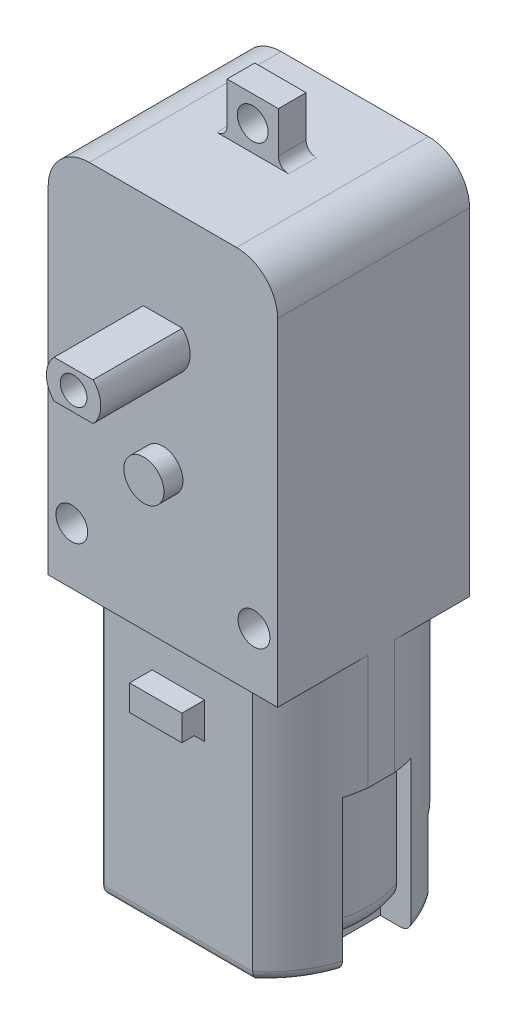
SolidWorks part; units mm, degrees
ref_plane "Front Plane" through (0, 0, 0) normal (0, 0, 1) x (1, 0, 0)
ref_plane "Top Plane" through (0, 0, 0) normal (0, 1, 0) x (1, 0, 0)
ref_plane "Right Plane" through (0, 0, 0) normal (1, 0, 0) x (0, 0, -1)
sketch "Sketch1" plane through (0, 0, 0) normal (0, 0, 1) x (1, 0, 0)
  line L0 (0, -7.1) -> (0, 11.3) construction
  line L1 (-11.175, -25.5) -> (11.175, -25.5)
  line L2 (-11.175, -25.5) -> (-11.175, 7.3)
  line L3 (-7.175, 11.3) -> (7.175, 11.3)
  line L4 (11.175, -25.5) -> (11.175, 7.3)
  line L5 (-11.175, -25.5) -> (11.175, 11.3) construction
  line L6 (-11.175, 11.3) -> (11.175, -25.5) construction
  arc A0 (7.175, 11.3) -> (11.175, 7.3) centre (7.175, 7.3) cw
  arc A1 (-11.175, 7.3) -> (-7.175, 11.3) centre (-7.175, 7.3) cw
  circle A2 centre (-8.875, -20) radius 1.55
  circle A3 centre (8.875, -20) radius 1.55
  point P0 (0, -7.1)
  dimension "D4" = 4
  dimension "D5" = 3.1
  dimension "D1" = 22.35
  dimension "D2" = 36.8
  dimension "D3" = 11.3
  dimension "D6" = 2.3
  dimension "D7" = 5.5
extrude "Boss-Extrude1" add sketch "Sketch1" against normal blind 8.6 and the other way blind 10.1
sketch "Sketch2" plane through (0, 0, 10.1) normal (0, 0, 1) x (1, 0, 0)
  line L1 (-1.8974, 1.85) -> (1.8974, 1.85)
  line L3 (-1.8974, -1.85) -> (1.8974, -1.85)
  line L5 (-1.8974, 1.85) -> (1.8974, -1.85) construction
  line L6 (-1.8974, -1.85) -> (1.8974, 1.85) construction
  arc A0 (-1.8974, 1.85) -> (-1.8974, -1.85) centre (0, 0) ccw
  arc A1 (1.8974, -1.85) -> (1.8974, 1.85) centre (0, 0) ccw
  point P0 (0, 0)
  point P8 (-1.9098, 1.8372)
  dimension "D2" = 5.3
  dimension "D1" = 3.7
extrude "Boss-Extrude2" add sketch "Sketch2" along normal blind 8.7
sketch "Sketch3" plane through (0, 0, 10.1) normal (0, 0, 1) x (1, 0, 0)
  line L0 (-11.175, -25.5) -> (11.175, -25.5) construction
  circle A0 centre (0, -11) radius 1.95
  point P4 (0, 0)
  dimension "D1" = 3.9
  dimension "D2" = 14.5
extrude "Boss-Extrude3" add sketch "Sketch3" along normal blind 1.85
sketch "Sketch4" plane through (0, -25.5, 0) normal (0, -1, 0) x (1, 0, 0)
  line L1 (-7.2528, -8.6) -> (7.2528, -8.6)
  line L2 (-11.175, -1.2969) -> (-11.175, 1.2969)
  line L3 (-7.2528, 8.6) -> (7.2528, 8.6)
  line L4 (11.175, -1.2969) -> (11.175, 1.2969)
  line L5 (-11.175, -8.6) -> (11.175, -8.6) construction
  line L6 (-11.175, 10.1) -> (-11.175, -8.6) construction
  line L7 (0, 8.6) -> (0, -8.6) construction
  line L8 (11.175, 10.1) -> (11.175, -8.6) construction
  arc A0 (-7.2528, 8.6) -> (-11.175, 1.2969) centre (0, 0) ccw
  arc A1 (7.2528, -8.6) -> (11.175, -1.2969) centre (0, 0) ccw
  arc A2 (11.175, 1.2969) -> (7.2528, 8.6) centre (0, 0) ccw
  arc A3 (-11.175, -1.2969) -> (-7.2528, -8.6) centre (0, 0) ccw
  point P1 (7.2909, -8.6)
  point P9 (0, 0)
  point P10 (-11.175, 1.2969)
  point P20 (11.175, 1.2969)
  dimension "D1" = 22.5
extrude "Boss-Extrude4" add sketch "Sketch4" along normal blind 26
sketch "Sketch5" plane through (0, 0, -8.6) normal (0, 0, -1) x (-1, 0, 0)
  line L0 (7.2528, -51.5) -> (-7.2528, -51.5) construction
  line L1 (-2.55, -32.45) -> (2.55, -32.45)
  line L2 (-2.55, -32.45) -> (-2.55, -29.95)
  line L3 (-2.55, -29.95) -> (2.55, -29.95)
  line L4 (2.55, -32.45) -> (2.55, -29.95)
  line L5 (-2.55, -32.45) -> (2.55, -29.95) construction
  line L6 (-2.55, -29.95) -> (2.55, -32.45) construction
  point P0 (0, -31.2)
  point P7 (0, 0)
  dimension "D1" = 21.55
  dimension "D2" = 2.5
  dimension "D3" = 5.1
extrude "Boss-Extrude5" add sketch "Sketch5" along normal blind 2.2
mirror "Mirror1" about plane through (0, 0, 0) normal (0, 0, 1) of "Boss-Extrude5"
chamfer "Chamfer1" distance 1 angle 45 2 edges at (0, -32.45, 8.6) (0, -32.45, -8.6)
sketch "Sketch6" plane through (0, -51.5, 0) normal (0, -1, 0) x (1, 0, 0)
  line L0 (-11.175, 10.1) -> (-11.175, 1.2969) construction
  line L1 (-11.175, 3.35) -> (-9.316, 3.35)
  line L2 (-11.175, 3.35) -> (-11.175, -3.35)
  line L3 (-11.175, -3.35) -> (-9.316, -3.35)
  line L5 (0, 0) -> (0, 8.6) construction
  line L6 (7.2528, 8.6) -> (-7.2528, 8.6) construction
  line L7 (11.175, -3.35) -> (9.316, -3.35)
  line L8 (11.175, 3.35) -> (11.175, -3.35)
  line L9 (11.175, 3.35) -> (9.316, 3.35)
  line L10 (0, 0) -> (-11.175, 0) construction
  arc A0 (-9.316, 3.35) -> (-9.316, -3.35) centre (0, 0) ccw
  arc A1 (9.316, 3.35) -> (9.316, -3.35) centre (0, 0) cw
  dimension "D1" = 19.8
  dimension "D2" = 6.7
extrude "Cut-Extrude1" cut sketch "Sketch6" against normal blind 14.8
sketch "Sketch7" plane through (0, -51.5, 0) normal (0, -1, 0) x (1, 0, 0)
  line L0 (0, 0) -> (0, 8.6) construction
  line L1 (-10.7396, 3.35) -> (-7.7396, 3.35)
  line L2 (-10.7396, 3.35) -> (-10.7396, -3.35)
  line L3 (-10.7396, -3.35) -> (-7.7396, -3.35)
  line L4 (-7.7396, 3.35) -> (-7.7396, -3.35)
  line L5 (7.2528, 8.6) -> (-7.2528, 8.6) construction
  line L6 (7.7396, 3.35) -> (7.7396, -3.35)
  line L7 (10.7396, -3.35) -> (7.7396, -3.35)
  line L8 (10.7396, 3.35) -> (10.7396, -3.35)
  line L9 (10.7396, 3.35) -> (7.7396, 3.35)
  dimension "D1" = 3
extrude "Cut-Extrude2" cut sketch "Sketch7" against normal blind 1.5
fillet "Fillet1" radius 2 2 edges at (9.9, -50, 0) (-9.9, -50, 0)
sketch "Sketch8" plane through (0, 0, -8.6) normal (0, 0, -1) x (-1, 0, 0)
  line L0 (7.2528, -51.5) -> (-7.2528, -51.5) construction
  line L1 (-3.8, -43) -> (3.8, -43)
  line L2 (-3.8, -43) -> (-3.8, -51.5)
  line L3 (-3.8, -51.5) -> (3.8, -51.5)
  line L4 (3.8, -43) -> (3.8, -51.5)
  line L5 (-3.8, -43) -> (3.8, -51.5) construction
  line L6 (-3.8, -51.5) -> (3.8, -43) construction
  point P0 (0, -47.25)
  point P7 (0, 0)
  dimension "D1" = 7.6
  dimension "D2" = 8.5
extrude "Boss-Extrude6" add sketch "Sketch8" along normal blind 1.5
sketch "Sketch9" plane through (0, 0, -8.6) normal (0, 0, -1) x (-1, 0, 0)
  line L0 (10.7396, -51.5) -> (10.7396, -36.7) construction
  line L1 (3.8, -51.5) -> (10.7396, -51.5)
  line L2 (3.8, -51.5) -> (3.8, -44)
  line L3 (3.8, -44) -> (10.7396, -44)
  line L4 (10.7396, -51.5) -> (10.7396, -44)
  line L5 (0, 0) -> (0, -51.5) construction
  line L6 (-3.8, -51.5) -> (3.8, -51.5) construction
  line L7 (-10.7396, -51.5) -> (-10.7396, -44)
  line L8 (-3.8, -44) -> (-10.7396, -44)
  line L9 (-3.8, -51.5) -> (-3.8, -44)
  line L10 (-3.8, -51.5) -> (-10.7396, -51.5)
  dimension "D1" = 7.5
extrude "Cut-Extrude3" cut sketch "Sketch9" against normal blind 2
sketch "Sketch10" plane through (0, 0, -6.6) normal (0, 0, -1) x (-1, 0, 0)
  line L0 (-3.8, -51.5) -> (-3.8, -44) construction
  line L1 (-7.5, -46.5) -> (-3.8, -46.5)
  line L2 (-7.5, -46.5) -> (-7.5, -48.5)
  line L3 (-7.5, -48.5) -> (-3.8, -48.5)
  line L4 (-3.8, -46.5) -> (-3.8, -48.5)
  line L5 (-9.1106, -51.5) -> (-3.8, -51.5) construction
  line L6 (0, -43) -> (0, -51.5) construction
  line L7 (3.8, -43) -> (-3.8, -43) construction
  line L8 (-3.8, -51.5) -> (3.8, -51.5) construction
  line L9 (3.8, -46.5) -> (3.8, -48.5)
  line L10 (7.5, -48.5) -> (3.8, -48.5)
  line L11 (7.5, -46.5) -> (7.5, -48.5)
  line L12 (7.5, -46.5) -> (3.8, -46.5)
  dimension "D1" = 2
  dimension "D2" = 3.7
  dimension "D3" = 3
extrude "Boss-Extrude7" add sketch "Sketch10" along normal blind 1
fillet "Fillet2" radius 1.5 1 edges at (0, -51.5, -10.1)
sketch "Sketch11" plane through (0, -51.5, 0) normal (0, -1, 0) x (1, 0, 0)
  line L0 (-2.5239, 4.2) -> (2.5239, 4.2)
  line L1 (0, -4.9) -> (0, 4.2) construction
  arc A0 (-2.5239, 4.2) -> (2.5239, 4.2) centre (0, 0) ccw
  dimension "D1" = 9.8
  dimension "D2" = 9.1
extrude "Boss-Extrude8" add sketch "Sketch11" along normal blind 1
sketch "Sketch12" plane through (0, -52.5, 0) normal (0, -1, 0) x (1, 0, 0)
  circle A0 centre (0, 0) radius 1
  dimension "D1" = 2
extrude "Boss-Extrude9" add sketch "Sketch12" along normal blind 1
sketch "Sketch13" plane through (0, 0, 18.8) normal (0, 0, 1) x (1, 0, 0)
  circle A0 centre (0, 0) radius 1.3
  dimension "D1" = 2.6
extrude "Cut-Extrude4" cut sketch "Sketch13" against normal up to surface (8.7 mm away) up to face at (-1.95, -11, 10.1)
sketch "Sketch14" plane through (0, 0, 0) normal (0, 0, 1) x (1, 0, 0)
  line L0 (7.175, 11.3) -> (-7.175, 11.3) construction
  line L1 (-2.5, 16.3) -> (2.5, 16.3)
  line L2 (-2.5, 16.3) -> (-2.5, 11.3)
  line L3 (-2.5, 11.3) -> (2.5, 11.3)
  line L4 (2.5, 16.3) -> (2.5, 11.3)
  line L5 (-2.5, 16.3) -> (2.5, 11.3) construction
  line L6 (-2.5, 11.3) -> (2.5, 16.3) construction
  circle A0 centre (0, 13.8) radius 1.5
  point P0 (0, 13.8)
  dimension "D2" = 3
  dimension "D1" = 5
extrude "Boss-Extrude10" add sketch "Sketch14" along normal mid plane 2.7
fillet "Fillet3" radius 1 8 edges at (9.3714, -51.5, 6.2242) (0, -51.5, 8.6) (-9.3714, -51.5, 6.2242) (-10.0573, -51.5, -5.0412) (10.0573, -51.5, -5.0412) (0, -43, -10.1) (2.5, 11.3, 0) (-2.5, 11.3, 0)
